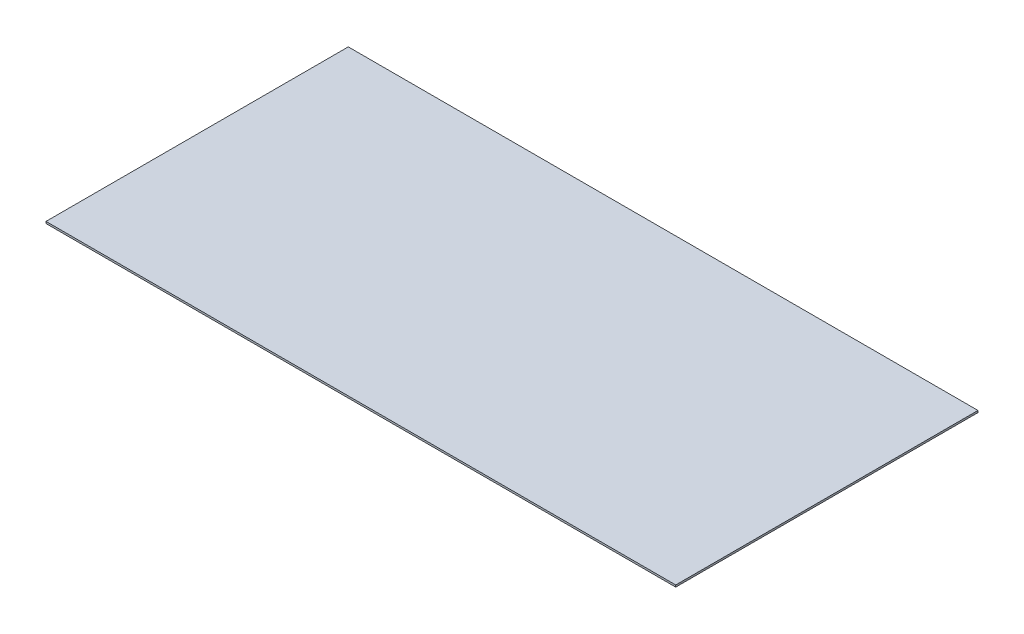
SolidWorks part; units mm, degrees
ref_plane "Front Plane" through (0, 0, 0) normal (0, 0, 1) x (1, 0, 0)
ref_plane "Top Plane" through (0, 0, 0) normal (0, 1, 0) x (1, 0, 0)
ref_plane "Right Plane" through (0, 0, 0) normal (1, 0, 0) x (0, 0, -1)
sketch "Sketch1" plane through (0, 0, 0) normal (0, 1, 0) x (1, 0, 0)
  line L1 (-25, -12) -> (25, -12)
  line L2 (-25, -12) -> (-25, 12)
  line L3 (-25, 12) -> (25, 12)
  line L4 (25, -12) -> (25, 12)
  line L5 (-25, -12) -> (25, 12) construction
  line L6 (-25, 12) -> (25, -12) construction
  point P0 (0, 0)
  dimension "D1" = 50
  dimension "D2" = 24
extrude "Boss-Extrude1" add sketch "Sketch1" along normal blind 0.15
